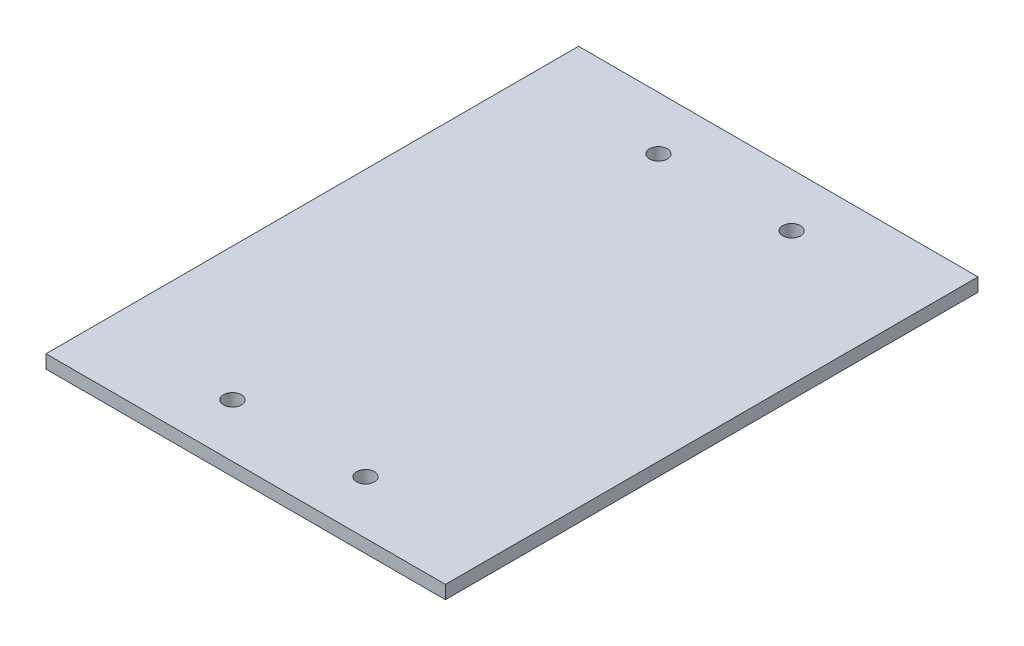
SolidWorks part; units mm, degrees
ref_plane "Front Plane" through (0, 0, 0) normal (0, 0, 1) x (1, 0, 0)
ref_plane "Top Plane" through (0, 0, 0) normal (0, 1, 0) x (1, 0, 0)
ref_plane "Right Plane" through (0, 0, 0) normal (1, 0, 0) x (0, 0, -1)
sketch "Sketch1" plane through (0, 0, 0) normal (0, 1, 0) x (1, 0, 0)
  line L0 (0, 50.8) -> (0, -50.8) construction
  line L1 (-38.1, 50.8) -> (38.1, 50.8)
  line L2 (-38.1, 50.8) -> (-38.1, -50.8)
  line L3 (-38.1, -50.8) -> (38.1, -50.8)
  line L4 (38.1, 50.8) -> (38.1, -50.8)
  line L5 (-38.1, 50.8) -> (38.1, -50.8) construction
  line L6 (-38.1, -50.8) -> (38.1, 50.8) construction
  line L7 (38.1, 0) -> (-38.1, 0) construction
  line L8 (-12.7, 40.64) -> (12.7, 40.64) construction
  circle A0 centre (-12.7, 40.64) radius 1.7
  circle A1 centre (12.7, 40.64) radius 1.7
  circle A2 centre (12.7, -40.64) radius 1.7
  circle A3 centre (-12.7, -40.64) radius 1.7
  point P0 (0, 0)
  point P14 (0, 40.64)
  dimension "D3" = 3.4
  dimension "D1" = 76.2
  dimension "D2" = 101.6
  dimension "D4" = 10.16
  dimension "D5" = 12.7
extrude "Boss-Extrude1" add sketch "Sketch1" along normal blind 2.54
